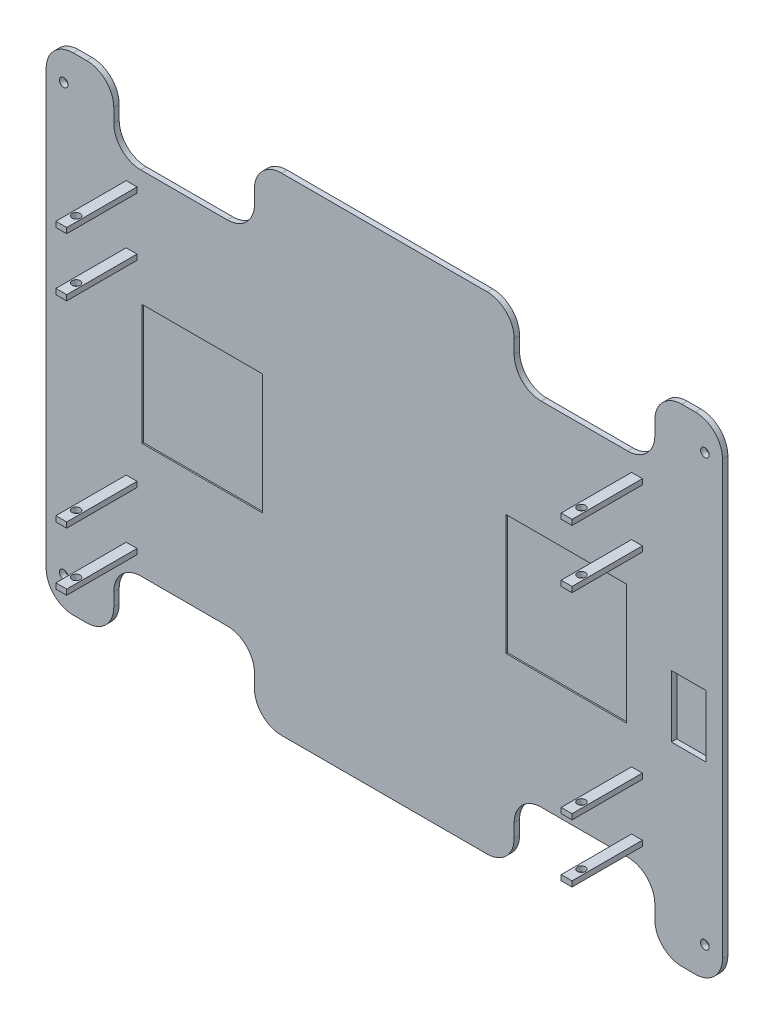
SolidWorks part; units mm, degrees
ref_plane "Plan de face" through (0, 0, 0) normal (0, 0, 1) x (1, 0, 0)
ref_plane "Plan de dessus" through (0, 0, 0) normal (0, 1, 0) x (1, 0, 0)
ref_plane "Plan de droite" through (0, 0, 0) normal (1, 0, 0) x (0, 0, -1)
sketch "Esquisse1" plane through (0, 0, 0) normal (0, 0, 1) x (1, 0, 0)
  line L1 (125, -90) -> (-125, -90)
  line L2 (125, -90) -> (125, 90)
  line L3 (125, 90) -> (-125, 90)
  line L4 (-125, -90) -> (-125, 90)
  line L5 (0, 90) -> (0, -90) construction
  line L6 (125, 0) -> (-125, 0) construction
  point P0 (0, 0)
  dimension "D1" = 180
  dimension "D2" = 250
extrude "Boss.-Extru.1" add sketch "Esquisse1" along normal blind 2
sketch "Esquisse2" plane through (0, 0, 2) normal (0, 0, 1) x (1, 0, 0)
  line L0 (0, 0) -> (0, 5.0767) construction
  line L1 (0, 0) -> (4.742, 0) construction
  line L3 (-100, 90) -> (-48, 90)
  line L4 (-100, 90) -> (-100, 65)
  line L5 (-100, 65) -> (-48, 65)
  line L6 (-48, 90) -> (-48, 65)
  line L7 (-74, 65) -> (-74, 90) construction
  line L8 (-100, 77.5) -> (-48, 77.5) construction
  line L12 (-100, -77.5) -> (-48, -77.5) construction
  line L13 (-74, -65) -> (-74, -90) construction
  line L14 (-48, -90) -> (-48, -65)
  line L15 (-100, -65) -> (-48, -65)
  line L16 (-100, -90) -> (-100, -65)
  line L17 (-100, -90) -> (-48, -90)
  line L18 (74, -65) -> (74, -90) construction
  line L19 (100, -77.5) -> (48, -77.5) construction
  line L20 (100, 77.5) -> (48, 77.5) construction
  line L21 (74, 65) -> (74, 90) construction
  line L22 (100, -90) -> (48, -90)
  line L23 (100, -90) -> (100, -65)
  line L24 (100, -65) -> (48, -65)
  line L25 (48, -90) -> (48, -65)
  line L26 (48, 90) -> (48, 65)
  line L27 (100, 65) -> (48, 65)
  line L28 (100, 90) -> (100, 65)
  line L29 (100, 90) -> (48, 90)
  line L55 (-125, 90) -> (-125, -90) construction
  line L58 (125, 90) -> (-125, 90) construction
  point P3 (-74, 77.5)
  point P21 (-74, -77.5)
  point P38 (74, -77.5)
  point P39 (74, 77.5)
  dimension "D1" = 25
  dimension "D2" = 52
  dimension "D3" = 25
extrude "Enlèv. mat.-Extru.1" cut sketch "Esquisse2" against normal through all contours L16 L17 L14 L15 | L25 L22 L23 L24 | L28 L29 L26 L27
fillet "Congé4" radius 10 20 edges at (125, 90, 1) (100, -90, 1) (100, -65, 1) (48, -65, 1) (48, -90, 1) (-48, -90, 1) (-48, -65, 1) (-100, -65, 1) (-100, -90, 1) (-125, -90, 1) (-125, 90, 1) (-100, 90, 1) (-100, 65, 1) (-48, 65, 1) (-48, 90, 1) (48, 90, 1) (48, 65, 1) (100, 65, 1) (100, 90, 1) (125, -90, 1)
sketch "Esquisse23" plane through (0, 0, 2) normal (0, 0, 1) x (1, 0, 0)
  line L1 (106.1263, -20.0719) -> (118.9263, -20.0719)
  line L2 (106.1263, -20.0719) -> (106.1263, 2.8281)
  line L3 (106.1263, 2.8281) -> (118.9263, 2.8281)
  line L4 (118.9263, -20.0719) -> (118.9263, 2.8281)
  line L5 (112.5263, 2.8281) -> (112.5263, -20.0719) construction
  line L6 (106.1263, -8.6219) -> (125.0742, -8.6219) construction
  point P0 (112.5263, -8.6219)
  point P5 (118.9263, -8.6219)
  dimension "D1" = 22.9
  dimension "D2" = 12.8
extrude "Enlèv. mat.-Extru.13" cut sketch "Esquisse23" against normal blind 2
sketch "Esquisse24" plane through (0, 0, 2) normal (0, 0, 1) x (1, 0, 0)
  line L0 (0, 0) -> (0, 29.2648) construction
  line L1 (-45.0608, -22.3) -> (-89.5608, -22.3)
  line L2 (-45.0608, -22.3) -> (-45.0608, 22.2)
  line L3 (-45.0608, 22.2) -> (-89.5608, 22.2)
  line L4 (-89.5608, -22.3) -> (-89.5608, 22.2)
  line L5 (-67.3108, 22.2) -> (-67.3108, -22.3) construction
  line L6 (-45.0608, -0.05) -> (-89.5608, -0.05) construction
  line L7 (45.0608, -22.3) -> (89.5608, -22.3)
  line L8 (45.0608, -22.3) -> (45.0608, 22.2)
  line L9 (45.0608, 22.2) -> (89.5608, 22.2)
  line L10 (89.5608, -22.3) -> (89.5608, 22.2)
  point P0 (-67.3108, -0.05)
  dimension "D1" = 44.5
  dimension "D2" = 44.5
extrude "Enlèv. mat.-Extru.14" cut sketch "Esquisse24" against normal blind 0.5
sketch "Esquisse27" plane through (0, 0, 2) normal (0, 0, 1) x (1, 0, 0)
sketch "Esquisse33" plane through (0, 0, 2) normal (0, 0, 1) x (1, 0, 0)
  line L1 (118.5057, -78.7621) -> (-118.5057, -78.7621) construction
  line L2 (118.5057, -78.7621) -> (118.5057, 78.7621) construction
  line L3 (118.5057, 78.7621) -> (-118.5057, 78.7621) construction
  line L4 (-118.5057, -78.7621) -> (-118.5057, 78.7621) construction
  circle A0 centre (-118.5057, 78.7621) radius 1.6
  circle A1 centre (118.5057, 78.7621) radius 1.6
  circle A2 centre (118.5057, -78.7621) radius 1.6
  circle A3 centre (-118.5057, -78.7621) radius 1.6
  point P0 (0, 0)
  dimension "D1" = 3.2
extrude "Enlèv. mat.-Extru.24" cut sketch "Esquisse33" against normal through all
sketch "Esquisse40" plane through (0, 0, 2) normal (0, 0, 1) x (1, 0, 0)
  line L0 (-125, 80) -> (-125, -80) construction
  line L1 (-91.4, -58.8749) -> (-95.4, -58.8749)
  line L2 (-91.4, -58.8749) -> (-91.4, -56.8749)
  line L3 (-91.4, -56.8749) -> (-95.4, -56.8749)
  line L4 (-95.4, -58.8749) -> (-95.4, -56.8749)
  line L5 (-93.4, -56.8749) -> (-93.4, -58.8749) construction
  line L6 (-91.4, -57.8749) -> (-95.4, -57.8749) construction
  line L7 (31.4758, 0) -> (0, 0) construction
  line L8 (0, 0) -> (0, 37.5679) construction
  line L9 (-91.4, 36.3749) -> (-95.4, 36.3749) construction
  line L10 (-91.4, -37.3749) -> (-95.4, -37.3749)
  line L11 (-91.4, -37.3749) -> (-91.4, -35.3749)
  line L12 (-91.4, -35.3749) -> (-95.4, -35.3749)
  line L13 (-95.4, -37.3749) -> (-95.4, -35.3749)
  line L14 (-93.4, -35.3749) -> (-93.4, -37.3749) construction
  line L15 (-91.4, -36.3749) -> (-95.4, -36.3749) construction
  line L16 (-93.4, 35.3749) -> (-93.4, 37.3749) construction
  line L17 (-91.4, 57.8749) -> (-95.4, 57.8749) construction
  line L18 (-93.4, 56.8749) -> (-93.4, 58.8749) construction
  line L19 (-95.4, 37.3749) -> (-95.4, 35.3749)
  line L20 (-91.4, 35.3749) -> (-95.4, 35.3749)
  line L21 (-91.4, 37.3749) -> (-91.4, 35.3749)
  line L22 (-91.4, 37.3749) -> (-95.4, 37.3749)
  line L23 (-95.4, 58.8749) -> (-95.4, 56.8749)
  line L24 (-91.4, 56.8749) -> (-95.4, 56.8749)
  line L25 (-91.4, 58.8749) -> (-91.4, 56.8749)
  line L26 (-91.4, 58.8749) -> (-95.4, 58.8749)
  line L27 (93.4, 56.8749) -> (93.4, 58.8749) construction
  line L28 (91.4, 57.8749) -> (95.4, 57.8749) construction
  line L29 (93.4, 35.3749) -> (93.4, 37.3749) construction
  line L30 (91.4, -36.3749) -> (95.4, -36.3749) construction
  line L31 (93.4, -35.3749) -> (93.4, -37.3749) construction
  line L32 (91.4, 36.3749) -> (95.4, 36.3749) construction
  line L33 (91.4, -57.8749) -> (95.4, -57.8749) construction
  line L34 (93.4, -56.8749) -> (93.4, -58.8749) construction
  line L35 (91.4, 58.8749) -> (95.4, 58.8749)
  line L36 (91.4, 58.8749) -> (91.4, 56.8749)
  line L37 (91.4, 56.8749) -> (95.4, 56.8749)
  line L38 (95.4, 58.8749) -> (95.4, 56.8749)
  line L39 (91.4, 37.3749) -> (95.4, 37.3749)
  line L40 (91.4, 37.3749) -> (91.4, 35.3749)
  line L41 (91.4, 35.3749) -> (95.4, 35.3749)
  line L42 (95.4, 37.3749) -> (95.4, 35.3749)
  line L43 (95.4, -37.3749) -> (95.4, -35.3749)
  line L44 (91.4, -35.3749) -> (95.4, -35.3749)
  line L45 (91.4, -37.3749) -> (91.4, -35.3749)
  line L46 (91.4, -37.3749) -> (95.4, -37.3749)
  line L47 (95.4, -58.8749) -> (95.4, -56.8749)
  line L48 (91.4, -56.8749) -> (95.4, -56.8749)
  line L49 (91.4, -58.8749) -> (91.4, -56.8749)
  line L50 (91.4, -58.8749) -> (95.4, -58.8749)
  point P0 (-93.4, -57.8749)
  point P8 (-93.4, -36.3749)
  point P29 (-93.4, 36.3749)
  point P30 (-93.4, 57.8749)
  point P63 (93.4, 57.8749)
  point P64 (93.4, 36.3749)
  point P65 (93.4, -36.3749)
  point P66 (93.4, -57.8749)
  dimension "D1" = 31.6
  dimension "D2" = 2
  dimension "D3" = 2
  dimension "D4" = 21.5
  dimension "D5" = 4
extrude "Boss.-Extru.12" add sketch "Esquisse40" along normal blind 26
sketch "Esquisse41" plane through (0, -58.8749, 0) normal (0, -1, 0) x (1, 0, 0)
  line L0 (-95.4, 28) -> (-91.4, 28) construction
  line L1 (0, 0) -> (0, 32.4213) construction
  line L2 (91.4, 28) -> (95.4, 28) construction
  circle A0 centre (-93.4, 22.52) radius 1.5
  circle A1 centre (93.4, 22.52) radius 1.5
  point P9 (-93.4, 28)
  point P12 (93.4, 28)
  dimension "D1" = 3
  dimension "D2" = 5.48
extrude "Enlèv. mat.-Extru.25" cut sketch "Esquisse41" against normal through all contours A0 | A1
sketch "Esquisse42" plane through (0, 0, 0) normal (0, 0, -1) x (-1, 0, 0)
  line L0 (-106.1263, -20.0719) -> (-118.9263, -20.0719) construction
  line L1 (-118.9263, -20.0719) -> (-118.9263, 2.8281) construction
  line L2 (-118.9263, 2.8281) -> (-106.1263, 2.8281) construction
  line L3 (-106.1263, 2.8281) -> (-106.1263, -20.0719) construction
  line L4 (-106.1263, -20.0719) -> (-118.9263, -20.0719)
  line L5 (-118.9263, -20.0719) -> (-118.9263, 2.8281)
  line L6 (-118.9263, 2.8281) -> (-106.1263, 2.8281)
  line L7 (-106.1263, 2.8281) -> (-106.1263, -20.0719)
extrude "Boss.-Extru.13" add sketch "Esquisse42" along normal blind 5 separate body
